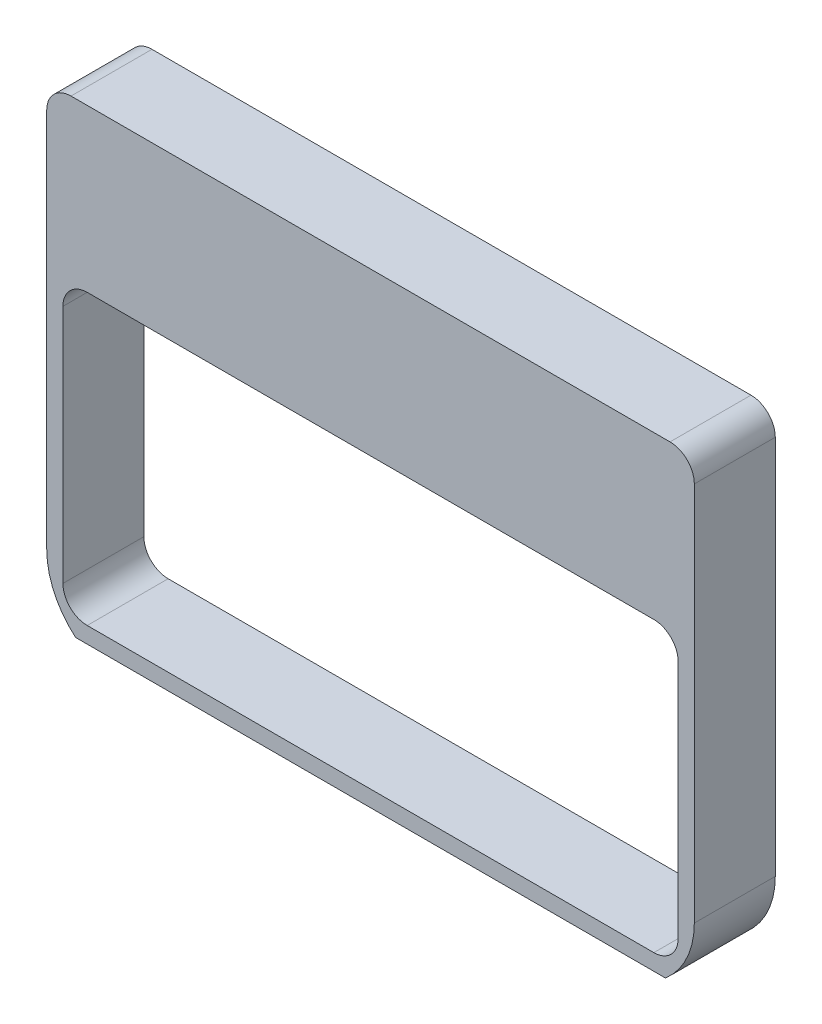
SolidWorks part; units mm, degrees
material "ABS"
ref_plane "Plano frontal" through (0, 0, 0) normal (0, 0, 1) x (1, 0, 0)
ref_plane "Plano superior" through (0, 0, 0) normal (0, 1, 0) x (1, 0, 0)
ref_plane "Plano direito" through (0, 0, 0) normal (1, 0, 0) x (0, 0, -1)
sketch "Esboço1" plane through (0, 0, 0) normal (0, 0, 1) x (1, 0, 0)
  line L0 (27.4361, 75.3989) -> (-52.5639, 75.3989)
  line L1 (-52.5639, 93.3989) -> (-1078.0639, 93.3989) construction
  line L2 (-49.5639, 93.3989) -> (24.4361, 93.3989)
  line L3 (27.4361, 78.3989) -> (27.4361, 43.4189)
  line L4 (-12.5639, 93.3989) -> (-12.5639, -3.5197) construction
  line L5 (23.864, 35.7585) -> (-48.9918, 35.7585)
  line L6 (-52.5639, 78.3989) -> (-52.5639, 43.4189)
  line L8 (22.4361, 73.3989) -> (-47.5639, 73.3989)
  line L9 (25.4361, 70.3989) -> (25.4361, 40.7585)
  line L10 (22.4361, 37.7585) -> (-47.5639, 37.7585)
  line L11 (-50.5639, 70.3989) -> (-50.5639, 40.7585)
  line L13 (1061.9361, 93.3989) -> (27.4361, 93.3989) construction
  line L14 (-52.5639, 78.3989) -> (-52.5639, 90.3989)
  line L19 (27.4361, 78.3989) -> (27.4361, 90.3989)
  arc A0 (-47.5639, 73.3989) -> (-50.5639, 70.3989) centre (-47.5639, 70.3989) ccw
  arc A1 (23.864, 35.7585) -> (27.4361, 43.4189) centre (17.4361, 43.4189) ccw
  arc A2 (24.4361, 93.3989) -> (27.4361, 90.3989) centre (24.4361, 90.3989) cw
  arc A3 (-52.5639, 90.3989) -> (-49.5639, 93.3989) centre (-49.5639, 90.3989) cw
  arc A4 (-48.9918, 35.7585) -> (-52.5639, 43.4189) centre (-42.5639, 43.4189) cw
  arc A5 (-47.5639, 37.7585) -> (-50.5639, 40.7585) centre (-47.5639, 40.7585) cw
  arc A6 (25.4361, 40.7585) -> (22.4361, 37.7585) centre (22.4361, 40.7585) cw
  arc A7 (22.4361, 73.3989) -> (25.4361, 70.3989) centre (22.4361, 70.3989) cw
  point P22 (-12.5639, 35.7585)
  point P33 (0, 0)
  point P45 (36.4361, 106.3989)
  point P46 (-52.5639, 106.3989)
  dimension "D1" = 0
  dimension "D2" = 3
  dimension "D5" = 18
  dimension "D7" = 2
  dimension "D8" = 2
  dimension "D9" = 2
  dimension "D3" = 10
  dimension "D10" = 3
  dimension "D4" = 0
  dimension "D6" = 2
extrude "Ressalto-extrusão1" add sketch "Esboço1" along normal blind 10 contours L19 A2 L2 A3 L14 L6 A4 L5 A1 L3
sketch "Esboço2" plane through (0, 0, 0) normal (0, 0, -1) x (-1, 0, 0)
  line L0 (49.5639, 93.3989) -> (-24.4361, 93.3989) construction
  line L1 (-22.4361, 73.3989) -> (47.5639, 73.3989)
  line L2 (-25.4361, 70.3989) -> (-25.4361, 40.7585)
  line L3 (-22.4361, 37.7585) -> (47.5639, 37.7585)
  line L4 (50.5639, 70.3989) -> (50.5639, 40.7585)
  line L5 (-23.864, 35.7585) -> (48.9918, 35.7585) construction
  line L6 (52.5639, 43.4189) -> (52.5639, 90.3989) construction
  line L7 (-27.4361, 43.4189) -> (-27.4361, 90.3989) construction
  arc A0 (47.5639, 73.3989) -> (50.5639, 70.3989) centre (47.5639, 70.3989) cw
  arc A1 (47.5639, 37.7585) -> (50.5639, 40.7585) centre (47.5639, 40.7585) ccw
  arc A2 (-25.4361, 40.7585) -> (-22.4361, 37.7585) centre (-22.4361, 40.7585) ccw
  arc A3 (-22.4361, 73.3989) -> (-25.4361, 70.3989) centre (-22.4361, 70.3989) ccw
  dimension "D5" = 3
  dimension "D1" = 20
  dimension "D2" = 2
  dimension "D3" = 2
  dimension "D4" = 2
extrude "Corte-extrusão1" cut sketch "Esboço2" against normal blind 10
